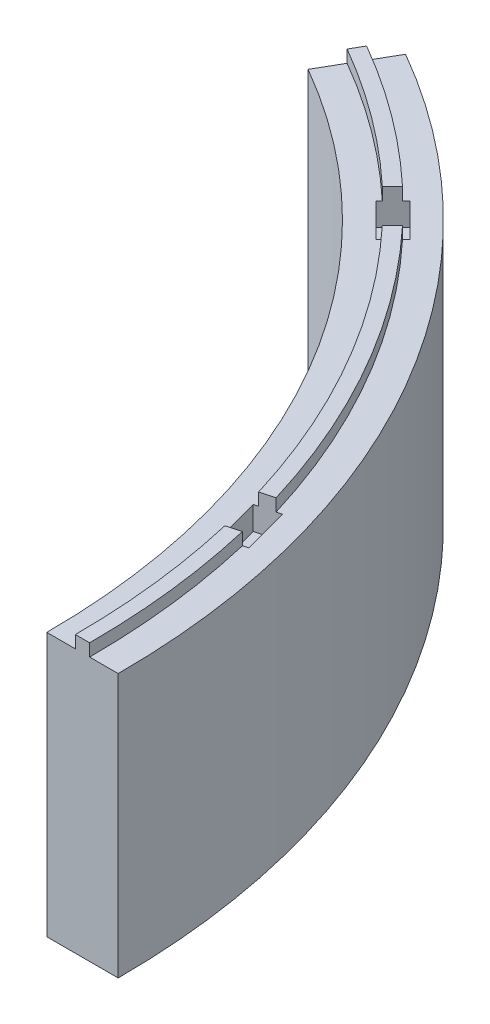
SolidWorks part; units mm, degrees
ref_plane "Ebene vorne" through (0, 0, 0) normal (0, 0, 1) x (1, 0, 0)
ref_plane "Ebene oben" through (0, 0, 0) normal (0, 1, 0) x (1, 0, 0)
ref_plane "Ebene rechts" through (0, 0, 0) normal (1, 0, 0) x (0, 0, -1)
sketch "Skizze1" plane through (0, 0, 0) normal (0, 1, 0) x (1, 0, 0)
  line L0 (0, 0) -> (165, 0) construction
  line L1 (165, 0) -> (0, 0) construction
  line L2 (0, 0) -> (82.5, 142.8942) construction
  line L3 (75, 129.9038) -> (82.5, 142.8942)
  line L4 (150, 0) -> (165, 0)
  arc A0 (82.5, 142.8942) -> (165, 0) centre (0, 0) cw
  arc A1 (75, 129.9038) -> (150, 0) centre (0, 0) cw
  dimension "D1" = 165
  dimension "D2" = 150
  dimension "D3" = 60
extrude "Aufsatz-Linear austragen1" add sketch "Skizze1" along normal blind 55.4
sketch "Skizze2" plane through (0, 55.4, 0) normal (0, 1, 0) x (1, 0, 0)
  line L0 (150, 0) -> (165, 0) construction
  line L1 (82.5, 142.8942) -> (75, 129.9038) construction
  line L2 (78, 135.1) -> (79.5, 137.698)
  line L3 (156, 0) -> (159, 0)
  arc A0 (159, 0) -> (79.5, 137.698) centre (0, 0) ccw
  arc A1 (156, 0) -> (78, 135.1) centre (0, 0) ccw
  dimension "D1" = 3
  dimension "D2" = 6
extrude "Aufsatz-Linear austragen2" add sketch "Skizze2" along normal blind 2.6
sketch "Skizze3" plane through (0, 58, 0) normal (0, 1, 0) x (1, 0, 0)
  line L0 (156, 0) -> (159, 0) construction
  line L1 (79.5, 137.698) -> (78, 135.1) construction
  line L2 (0, 0) -> (152.1333, 40.764) construction
  line L3 (0, 0) -> (111.3693, 111.3693) construction
  line L4 (150, 0) -> (156, 0) construction
  line L5 (148.4244, 44.9466) -> (153.254, 46.2407)
  line L6 (153.254, 46.2407) -> (155.8422, 36.5814)
  line L7 (155.8422, 36.5814) -> (151.0126, 35.2873)
  line L8 (151.0126, 35.2873) -> (148.4244, 44.9466)
  line L9 (148.4244, 44.9466) -> (155.8422, 36.5814) construction
  line L10 (106.066, 113.1371) -> (109.6016, 116.6726)
  line L11 (109.6016, 116.6726) -> (116.6726, 109.6016)
  line L12 (116.6726, 109.6016) -> (113.1371, 106.066)
  line L13 (113.1371, 106.066) -> (106.066, 113.1371)
  line L14 (106.066, 113.1371) -> (116.6726, 109.6016) construction
  arc A0 (157.5, 0) -> (78.75, 136.399) centre (0, 0) ccw construction
  point P14 (152.1333, 40.764)
  point P19 (111.3693, 111.3693)
  dimension "D1" = 30
  dimension "D2" = 15
  dimension "D3" = 5
  dimension "D4" = 10
  dimension "D5" = 5
  dimension "D6" = 5
extrude "Schnitt-Linear austragen1" cut sketch "Skizze3" against normal blind 7.5
sketch "Skizze4" plane through (0, 0, 0) normal (0, -1, 0) x (1, 0, 0)
  line L0 (82.5, -142.8942) -> (75, -129.9038) construction
  line L1 (150, 0) -> (165, 0) construction
  line L2 (0, 0) -> (157.5, 0) construction
  line L3 (0, 0) -> (152.1333, -40.764) construction
  line L4 (0, 0) -> (111.3693, -111.3693) construction
  arc A0 (78.75, -136.399) -> (157.5, 0) centre (0, 0) ccw construction
  circle A1 centre (111.3693, -111.3693) radius 2.2
  circle A2 centre (152.1333, -40.764) radius 2.2
  dimension "D1" = 4.4
  dimension "D2" = 15
  dimension "D3" = 30
extrude "Schnitt-Linear austragen2" cut sketch "Skizze4" against normal blind 10
equation "\"D5@Skizze3\"=\"D4@Skizze3\"/2"
equation "\"D6@Skizze3\"=\"D5@Skizze3\""
